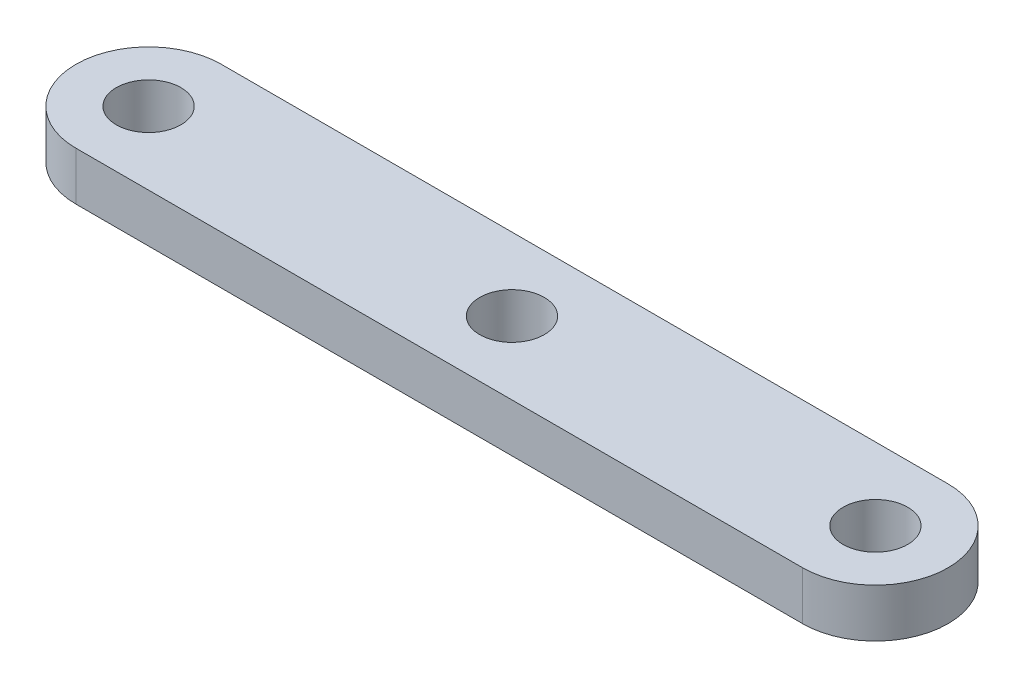
SolidWorks part; units mm, degrees
ref_plane "Front Plane" through (0, 0, 0) normal (0, 0, 1) x (1, 0, 0)
ref_plane "Top Plane" through (0, 0, 0) normal (0, 1, 0) x (1, 0, 0)
ref_plane "Right Plane" through (0, 0, 0) normal (1, 0, 0) x (0, 0, -1)
sketch "Sketch2" plane through (0, 0, 0) normal (0, 1, 0) x (1, 0, 0)
  line L1 (0, 0) -> (90, 0)
  line L3 (0, 18) -> (90, 18)
  arc A1 (0, 0) -> (0, 18) centre (0, 9) cw
  arc A2 (90, 0) -> (90, 18) centre (90, 9) ccw
  dimension "D1" = 18
  dimension "D2" = 90
extrude "Boss-Extrude1" add sketch "Sketch2" along normal blind 6
sketch "Sketch3" plane through (0, 0, 0) normal (0, -1, 0) x (1, 0, 0)
  line L0 (0, 0) -> (90, 0) construction
  line L1 (45, 0) -> (45, -18) construction
  line L2 (90, -18) -> (0, -18) construction
  circle A0 centre (0, -9) radius 4
  circle A2 centre (90, -9) radius 4
  circle A3 centre (45, -9) radius 4
  dimension "D1" = 9
  dimension "D2" = 8
extrude "Cut-Extrude1" cut sketch "Sketch3" against normal blind 6
